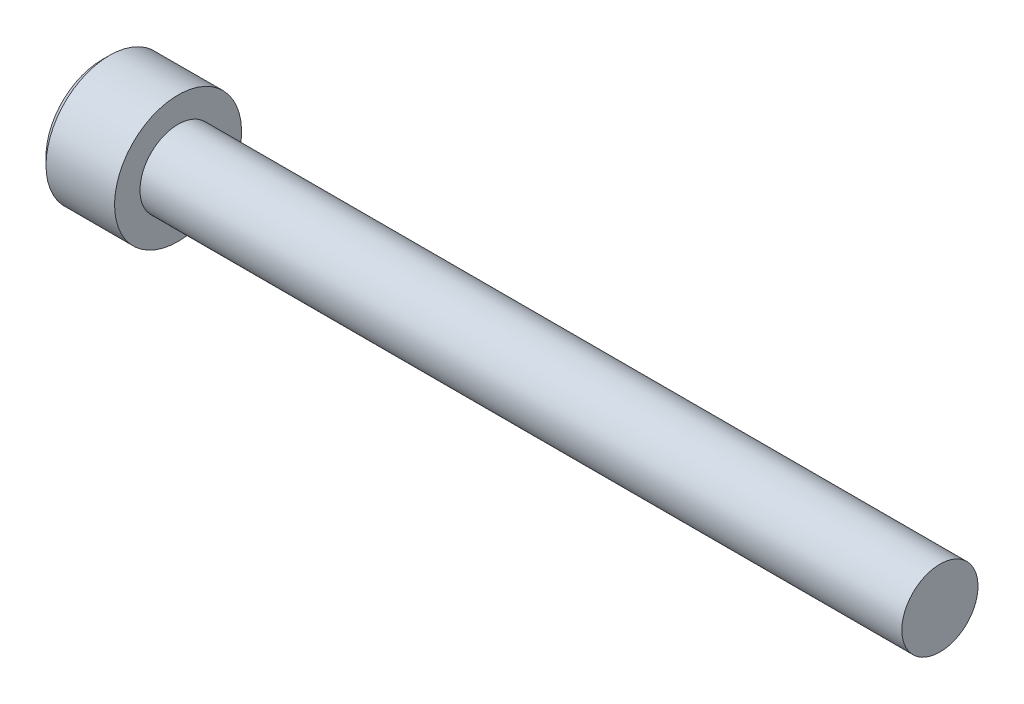
SolidWorks part; units mm, degrees
material "SCM435"
ref_plane "Front Plane" through (0, 0, 0) normal (0, 0, 1) x (1, 0, 0)
ref_plane "Top Plane" through (0, 0, 0) normal (0, 1, 0) x (1, 0, 0)
ref_plane "Right Plane" through (0, 0, 0) normal (1, 0, 0) x (0, 0, -1)
sketch "Sketch1" plane through (0, 0, 0) normal (0, 0, 1) x (1, 0, 0)
  line L0 (-6, 0) -> (60, 0) construction
  line L1 (-6, 0) -> (-6, 5)
  line L2 (-6, 5) -> (0, 5)
  line L3 (0, 5) -> (0, 3)
  line L4 (0, 3) -> (60, 3)
  line L5 (60, 3) -> (60, 0)
  line L6 (60, 0) -> (-6, 0)
  dimension "A" = 10
  dimension "M" = 6
  dimension "E" = 6
  dimension "L" = 60
revolve "Revolve1" add sketch "Sketch1" about L0
cosmetic thread "Thread1" parameters "L_s"=25, "ATD"=4.917
chamfer "Chamfer1" distance 0.6 1 edges at (-6, -5, 0)
sketch "Sketch2" plane through (0, 0, 0) normal (0, 0, 1) x (1, 0, 0)
  line L0 (-1.4978, 0) -> (-3, 2.5)
  line L1 (60, 0) -> (-6, 0) construction
  line L2 (-3, 2.5) -> (-6, 2.5)
  line L3 (-6, 0) -> (-6, 5) construction
  line L4 (-6, 2.5) -> (-6, 0)
  line L5 (-6, 0) -> (-1.4978, 0) construction
  line L6 (-1.4978, 0) -> (-6, 0)
  dimension "FIX_3" = 59
  dimension "MSM_2" = 3
revolve "Cut-Revolve1" cut sketch "Sketch2" about L5
sketch "Sketch3" plane through (-6, 0, 0) normal (-1, 0, 0) x (0, 0, 1)
  line L1 (0, 2.8868) -> (-2.5, 1.4434)
  line L2 (-2.5, 1.4434) -> (-2.5, -1.4434)
  line L3 (-2.5, -1.4434) -> (0, -2.8868)
  line L4 (0, -2.8868) -> (2.5, -1.4434)
  line L5 (2.5, -1.4434) -> (2.5, 1.4434)
  line L6 (2.5, 1.4434) -> (0, 2.8868)
  circle A0 centre (0, 0) radius 2.5 construction
extrude "Cut-Extrude1" cut sketch "Sketch3" against normal blind 3
